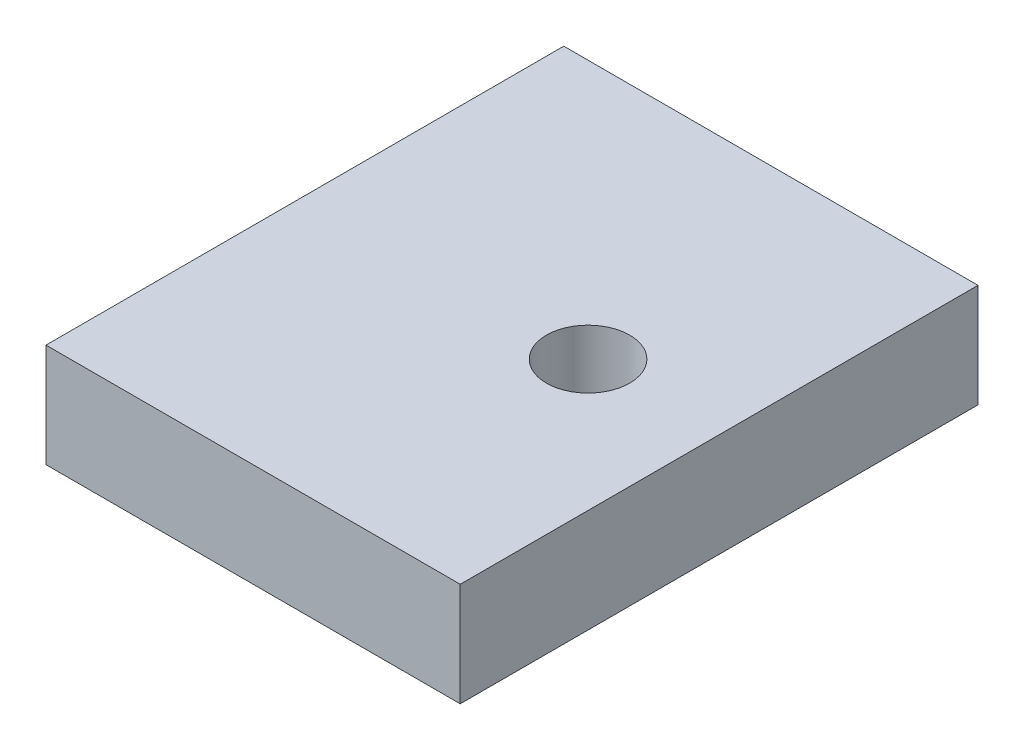
SolidWorks part; units mm, degrees
ref_plane "Front Plane" through (0, 0, 0) normal (0, 0, 1) x (1, 0, 0)
ref_plane "Top Plane" through (0, 0, 0) normal (0, 1, 0) x (1, 0, 0)
ref_plane "Right Plane" through (0, 0, 0) normal (1, 0, 0) x (0, 0, -1)
sketch "Sketch2" plane through (0, 0, 0) normal (0, 1, 0) x (1, 0, 0)
  line L1 (0, 0) -> (25.4, 0)
  line L2 (0, 0) -> (0, 31.75)
  line L3 (0, 31.75) -> (25.4, 31.75)
  line L12 (25.4, 31.75) -> (25.4, 0)
  dimension "D1" = 25.4
  dimension "D2" = 31.75
extrude "Boss-Extrude1" add sketch "Sketch2" along normal blind 6.35
hole_wizard "1/4-20 Tapped Hole1" positions "3DSketch1" profile "Sketch3" tap size "1/4-20" standard "ANSI Inch"
sketch3d "3DSketch1"
  line L0 (0, 6.35, -31.75) -> (25.4, 6.35, -31.75) construction
  line L1 (25.4, 6.35, -31.75) -> (25.4, 6.35, 0) construction
  point P0 (17.3645, 6.35, -15.875)
  dimension "D1" = 15.875
  dimension "D2" = 8.0355
sketch "Sketch3" plane through (17.3645, 6.35, -15.875) normal (1, 0, 0) x (0, 0, 1)
  line L0 (0, 0) -> (0, 20.5838)
  line L1 (0, 20.5838) -> (2.5527, 19.05)
  line L2 (2.5527, 19.05) -> (2.5527, 0)
  line L5 (2.5527, 0) -> (0, 0)
  line L10 (0, 20.5838) -> (-2.5527, 19.05) construction
  line L11 (0, -6.35) -> (0, 107.95) construction
  dimension "Tap Drill Dia." = 5.1054
  dimension "Tap Drill Depth" = 19.05
  dimension "Drill Angle" = 118
cosmetic thread "Hole Thread1" parameters "D1"=6.35, "D2"=6.35
